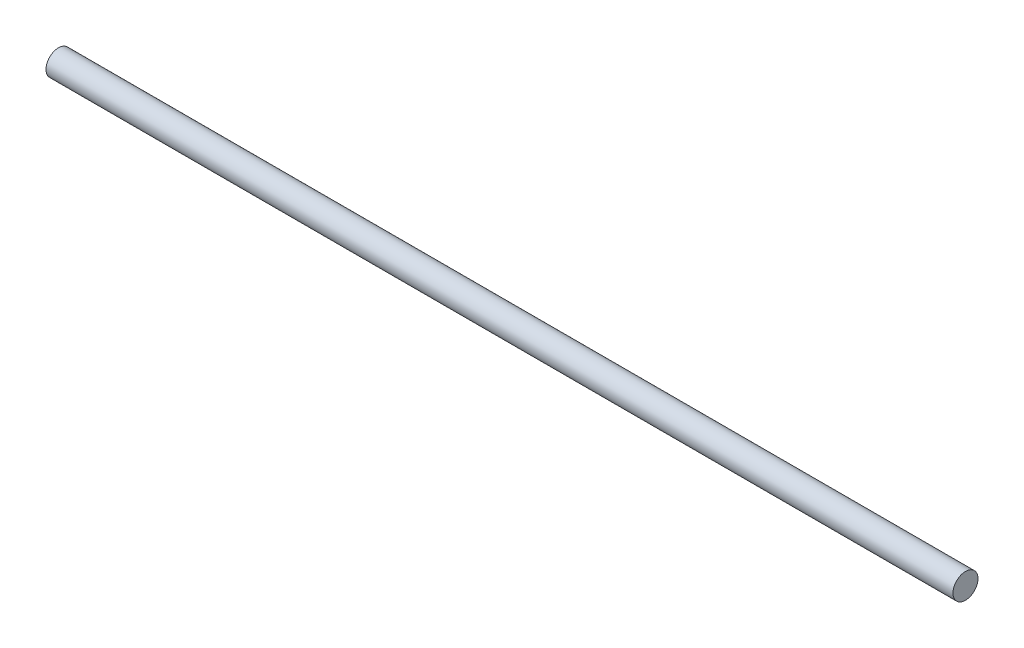
SolidWorks part; units mm, degrees
ref_plane "前视基准面" through (0, 0, 0) normal (0, 0, 1) x (1, 0, 0)
ref_plane "上视基准面" through (0, 0, 0) normal (0, 1, 0) x (1, 0, 0)
ref_plane "右视基准面" through (0, 0, 0) normal (1, 0, 0) x (0, 0, -1)
sketch "草图1" plane through (0, 0, 0) normal (1, 0, 0) x (0, 0, -1)
  circle A0 centre (0, 0) radius 4
  dimension "D1" = 8
extrude "凸台-拉伸1" add sketch "草图1" along normal blind 290
